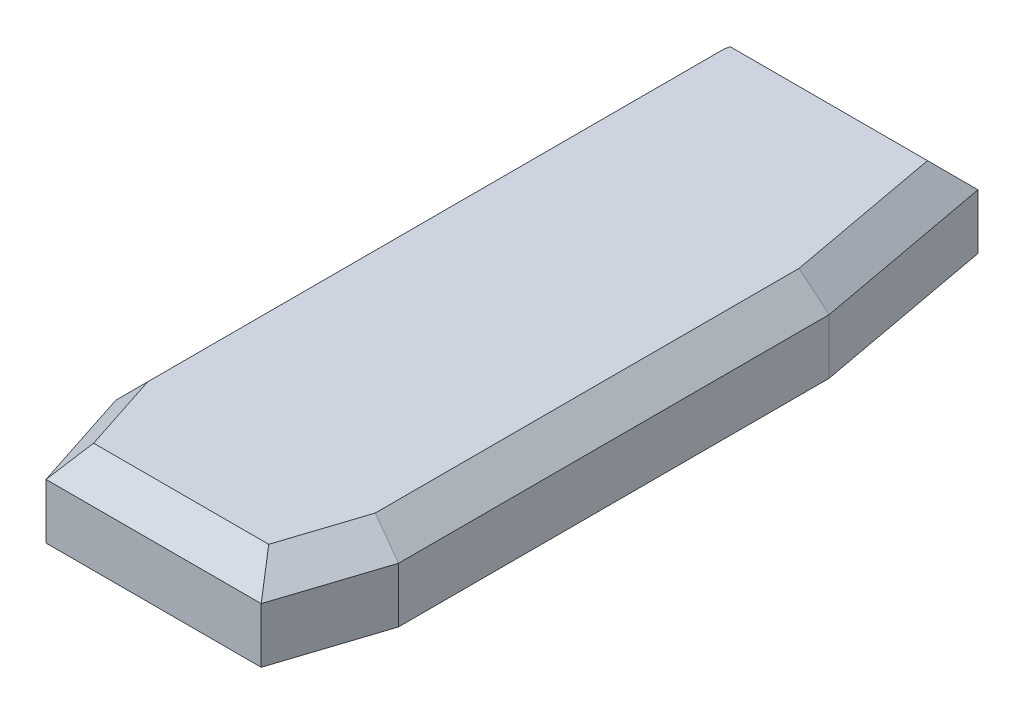
SolidWorks part; units mm, degrees
ref_plane "Спереди" through (0, 0, 0) normal (0, 0, 1) x (1, 0, 0)
ref_plane "Сверху" through (0, 0, 0) normal (0, 1, 0) x (1, 0, 0)
ref_plane "Справа" through (0, 0, 0) normal (1, 0, 0) x (0, 0, -1)
sketch "Эскиз1" plane through (0, 0, 0) normal (0, 1, 0) x (1, 0, 0)
  line L0 (-2.4445, 0) -> (-18.0555, 0)
  line L1 (-20.5, 7.5106) -> (-20.5, 38.7549)
  line L2 (-18.0555, 52) -> (-2.4445, 52)
  line L3 (0, 38.7549) -> (0, 7.5106)
  line L4 (-18.0555, 52) -> (-20.5, 38.7549)
  line L5 (-10.25, 52) -> (-10.25, 0) construction
  line L7 (-2.4445, 52) -> (0, 38.7549)
  line L8 (-20.5, 7.5106) -> (-18.0555, 0)
  line L9 (0, 7.5106) -> (-2.4445, 0)
extrude "Бобышка-Вытянуть1" add sketch "Эскиз1" along normal blind 6
chamfer "Фаска1" distance 2 angle 45 7 edges at (-10.25, 6, -52) (-1.2222, 6, -45.3775) (-20.5, 6, -23.1327) (0, 6, -23.1327) (-19.2778, 6, -3.7553) (-1.2222, 6, -3.7553) (-10.25, 6, 0)
